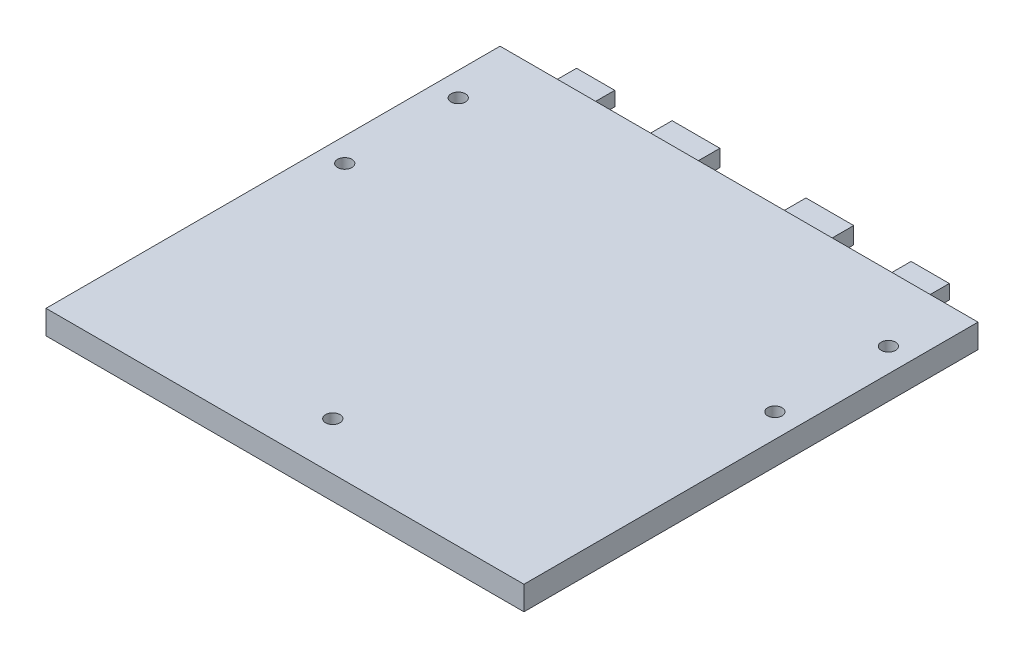
SolidWorks part; units mm, degrees
ref_plane "Front Plane" through (0, 0, 0) normal (0, 0, 1) x (1, 0, 0)
ref_plane "Top Plane" through (0, 0, 0) normal (0, 1, 0) x (1, 0, 0)
ref_plane "Right Plane" through (0, 0, 0) normal (1, 0, 0) x (0, 0, -1)
sketch "Sketch1" plane through (0, 0, 0) normal (0, 1, 0) x (1, 0, 0)
  line L1 (0, 0) -> (200, 0)
  line L2 (0, 0) -> (0, 190)
  line L3 (0, 190) -> (200, 190)
  line L4 (200, 0) -> (200, 190)
  dimension "D1" = 190
  dimension "D2" = 200
extrude "Boss-Extrude1" add sketch "Sketch1" along normal blind 10
sketch "Sketch2" plane through (0, 0, -190) normal (0, 0, -1) x (-1, 0, 0)
  line L0 (-200, 10) -> (0, 10) construction
  line L5 (-200, 0) -> (0, 0) construction
  line L12 (0, 10) -> (0, 0) construction
  line L13 (-20, 0) -> (-40, 0)
  line L14 (-20, 0) -> (-20, 10)
  line L15 (-20, 10) -> (-40, 10)
  line L16 (-40, 0) -> (-40, 10)
  line L17 (0, 10) -> (-100, 10) construction
  line L18 (-22, 8) -> (-38, 8)
  line L19 (-22, 8) -> (-22, 2)
  line L20 (-22, 2) -> (-38, 2)
  line L21 (-38, 8) -> (-38, 2)
  line L22 (-100, 10) -> (-100, -21.092) construction
  line L23 (-178, 2) -> (-162, 2)
  line L24 (-162, 8) -> (-162, 2)
  line L25 (-178, 8) -> (-162, 8)
  line L26 (-178, 8) -> (-178, 2)
  line L27 (-138, 9) -> (-118, 9)
  line L32 (-62, 2) -> (-82, 2)
  line L33 (-62, 2) -> (-62, 9)
  line L34 (-62, 9) -> (-82, 9)
  line L35 (-82, 2) -> (-82, 9)
  line L36 (-118, 2) -> (-118, 9)
  line L37 (-138, 2) -> (-118, 2)
  line L38 (-138, 2) -> (-138, 9)
  point P26 (-40, 5)
  dimension "D1" = 20
  dimension "D2" = 22
  dimension "D3" = 2
  dimension "D4" = 20
  dimension "D5" = 2
  dimension "D6" = 2
  dimension "D7" = 2
  dimension "D8" = 2
  dimension "D9" = 2
  dimension "D10" = 20
  dimension "D11" = 2
  dimension "D12" = 2
  dimension "D13" = 2
  dimension "D14" = 1
  dimension "D15" = 2
  dimension "D16" = 7
  dimension "D17" = 6
  dimension "D18" = 18
  dimension "D19" = 62
extrude "Boss-Extrude2" add sketch "Sketch2" along normal blind 10 contours L19 L18 L21 L20 | L33 L32 L35 L34 | L27 L36 L37 L38 | L23 L24 L25 L26
sketch "Sketch3" plane through (0, 10, 0) normal (0, 1, 0) x (1, 0, 0)
  line L0 (200, 0) -> (200, 190) construction
  line L1 (0, 0) -> (200, 0)
  line L2 (0, 0) -> (0, 10)
  line L4 (200, 0) -> (200, 10)
  line L5 (100, 190) -> (100, 0) construction
  line L6 (200, 190) -> (0, 190) construction
  circle A0 centre (190, 162.5) radius 3
  circle A1 centre (190, 115) radius 3
  circle A4 centre (10, 162.5) radius 3
  circle A5 centre (10, 115) radius 3
  circle A6 centre (100, 10) radius 3
  dimension "D2" = 6
  dimension "D3" = 10
  dimension "D4" = 6
  dimension "D5" = 10
  dimension "D7" = 10
  dimension "D6" = 6
  dimension "D8" = 162.5
  dimension "D9" = 115
  dimension "D1" = 10
extrude "Cut-Extrude1" cut sketch "Sketch3" against normal blind 10 contours A1 | A0 | A5 | A4
sketch "Sketch4" plane through (0, 10, 0) normal (0, 1, 0) x (1, 0, 0)
  line L0 (100, 0) -> (100, 76.4766) construction
  line L1 (0, 0) -> (200, 0) construction
  circle A0 centre (100, 20) radius 3
  dimension "D1" = 6
  dimension "D2" = 20
extrude "Cut-Extrude2" cut sketch "Sketch4" against normal blind 10
